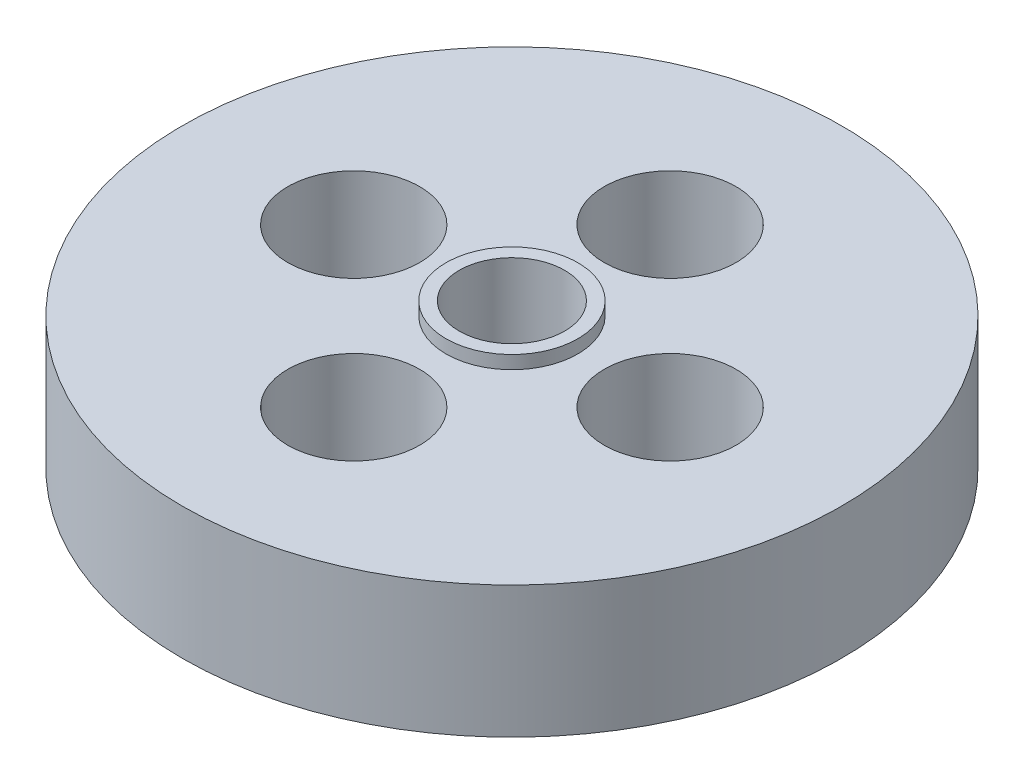
SolidWorks part; units mm, degrees
ref_plane "Front Plane" through (0, 0, 0) normal (0, 0, 1) x (1, 0, 0)
ref_plane "Top Plane" through (0, 0, 0) normal (0, 1, 0) x (1, 0, 0)
ref_plane "Right Plane" through (0, 0, 0) normal (1, 0, 0) x (0, 0, -1)
sketch "Sketch1" plane through (0, 0, 0) normal (0, 1, 0) x (1, 0, 0)
  line L0 (-25, 0) -> (-17, 0) construction
  line L1 (-7, 0) -> (7, 0) construction
  line L2 (0, 12.749) -> (0, 12) construction
  line L3 (0, 7) -> (0, -7) construction
  line L4 (17, 0) -> (25, 0) construction
  line L5 (0, -17) -> (0, -25) construction
  circle A0 centre (0, 0) radius 25
  arc A1 (-10.9583, -4.8903) -> (-4.8903, -10.9583) centre (0, 0) ccw
  circle A2 centre (0, 12) radius 5
  circle A3 centre (0, 0) radius 4
  circle A4 centre (12, 0) radius 5
  circle A5 centre (0, -12) radius 5
  circle A6 centre (-12, 0) radius 5
  arc A7 (-4.8903, 10.9583) -> (-10.9583, 4.8903) centre (0, 0) ccw
  arc A8 (10.9583, 4.8903) -> (4.8903, 10.9583) centre (0, 0) ccw
  arc A9 (4.8903, -10.9583) -> (10.9583, -4.8903) centre (0, 0) ccw
  point P20 (0, 0)
  dimension "D1" = 4
extrude "Boss-Extrude1" add sketch "Sketch1" along normal blind 10 contours A0 A9 A5 A1 A6 A7 A2 A8 A4 | A5 A9 A4 A8 A2 A7 A6 A1 A3
sketch "Sketch2" plane through (0, 10, 0) normal (0, 1, 0) x (1, 0, 0)
  circle A0 centre (0, 0) radius 5
extrude "Boss-Extrude2" add sketch "Sketch2" along normal blind 1
sketch "Sketch3" plane through (0, 10, 0) normal (0, -1, 0) x (1, 0, 0)
  circle A1 centre (0, 0) radius 4
  circle A2 centre (0, 0) radius 4
  dimension "D1" = 0
extrude "Cut-Extrude1" cut sketch "Sketch3" against normal blind 83
